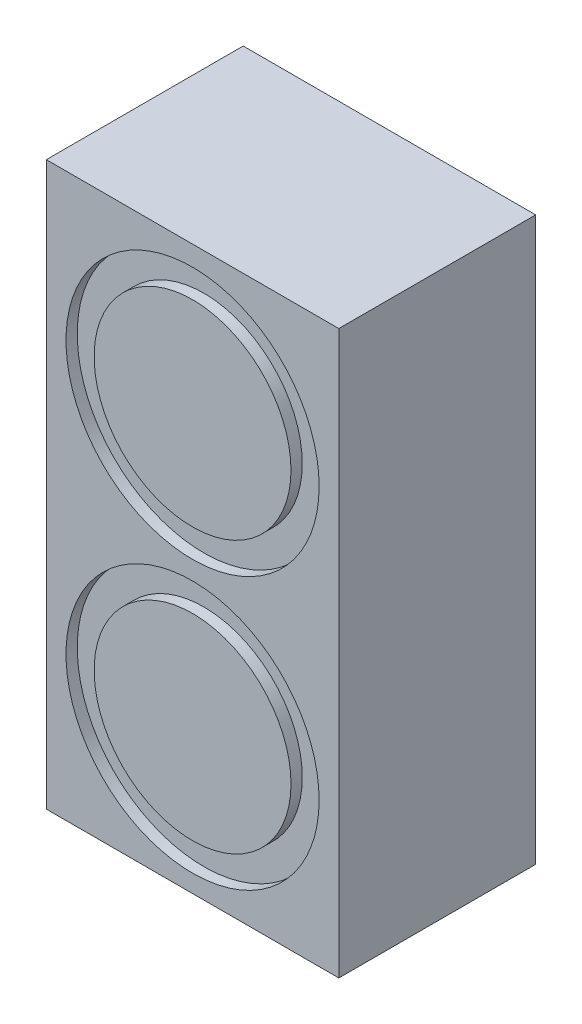
SolidWorks part; units mm, degrees
ref_plane "前基準面" through (0, 0, 0) normal (0, 0, 1) x (1, 0, 0)
ref_plane "上基準面" through (0, 0, 0) normal (0, 1, 0) x (1, 0, 0)
ref_plane "右基準面" through (0, 0, 0) normal (1, 0, 0) x (0, 0, -1)
sketch "草圖1" plane through (0, 0, 0) normal (0, 0, 1) x (1, 0, 0)
  line L1 (-30.9416, 28.2779) -> (21.0584, 28.2779)
  line L2 (-30.9416, 28.2779) -> (-30.9416, -71.7221)
  line L3 (-30.9416, -71.7221) -> (21.0584, -71.7221)
  line L4 (21.0584, 28.2779) -> (21.0584, -71.7221)
  dimension "D1" = 100
  dimension "D2" = 52
extrude "填料-伸長1" add sketch "草圖1" along normal blind 35
sketch "草圖2" plane through (0, 0, 35) normal (0, 0, 1) x (1, 0, 0)
  line L0 (-4.9416, 28.2779) -> (-4.9416, -71.7221) construction
  line L1 (21.0584, 28.2779) -> (-30.9416, 28.2779) construction
  line L2 (-30.9416, -71.7221) -> (21.0584, -71.7221) construction
  circle A0 centre (-4.9416, 2.2248) radius 22.5
  circle A1 centre (-4.9416, -46.0831) radius 22.5
  circle A2 centre (-4.9416, 2.2248) radius 17.5
  circle A3 centre (-4.9416, -46.0831) radius 17.5
  dimension "D1" = 45
  dimension "D2" = 45
  dimension "D3" = 35
  dimension "D4" = 35
extrude "除料-伸長1" cut sketch "草圖2" against normal blind 2
